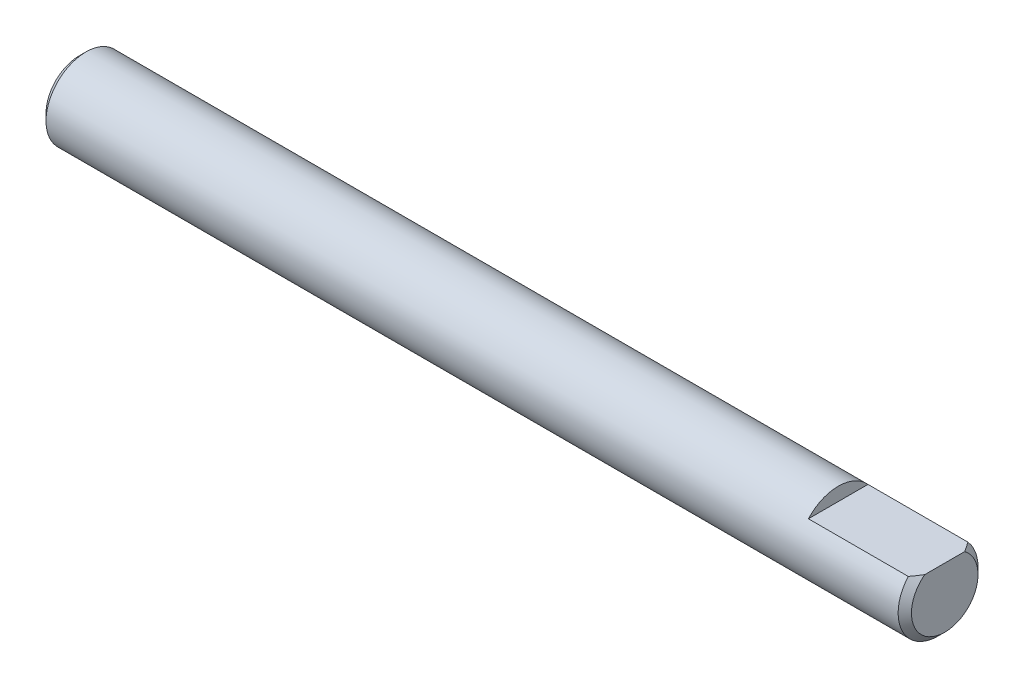
SolidWorks part; units mm, degrees
ref_plane "Front Plane" through (0, 0, 0) normal (0, 0, 1) x (1, 0, 0)
ref_plane "Top Plane" through (0, 0, 0) normal (0, 1, 0) x (1, 0, 0)
ref_plane "Right Plane" through (0, 0, 0) normal (1, 0, 0) x (0, 0, -1)
sketch "Sketch1" plane through (0, 0, 0) normal (1, 0, 0) x (0, 0, -1)
  circle A0 centre (0, 0) radius 3
  dimension "D1" = 6
extrude "Boss-Extrude1" add sketch "Sketch1" along normal mid plane 65
sketch "Sketch2" plane through (32.5, 0, 0) normal (1, 0, 0) x (0, 0, -1)
  line L0 (-2.2361, 2) -> (2.2361, 2)
  circle A1 centre (0, 0) radius 3
  arc A2 (2.2361, 2) -> (-2.2361, 2) centre (0, 0) ccw
  point P5 (0, 2)
  dimension "D2" = 2
  dimension "D1" = 0
extrude "Cut-Extrude1" cut sketch "Sketch2" against normal blind 8
chamfer "Chamfer1" distance 0.5 angle 45 2 edges at (-32.5, 0, -3) (32.5, -3, 0)
